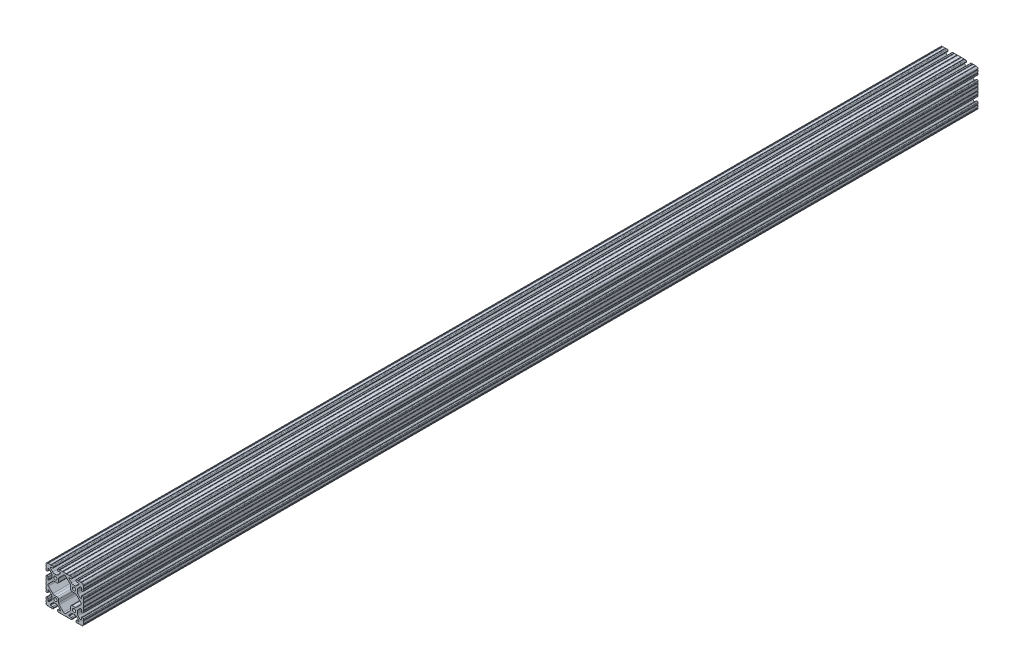
SolidWorks part; units mm, degrees
material "6105-T5 Aluminum"
ref_plane "Front Plane" through (0, 0, 0) normal (0, 0, 1) x (1, 0, 0)
ref_plane "Top Plane" through (0, 0, 0) normal (0, 1, 0) x (1, 0, 0)
ref_plane "Right Plane" through (0, 0, 0) normal (1, 0, 0) x (0, 0, -1)
sketch "Sketch1" plane through (0, 0, 0) normal (0, 0, 1) x (1, 0, 0)
  line L0 (15.487, 12.312) -> (20.9469, 12.312)
  line L1 (24.3055, 10.9208) -> (33.1609, 2.0655)
  line L2 (33.1609, -2.0655) -> (24.3055, -10.9208)
  line L3 (20.9469, -12.312) -> (15.487, -12.312)
  line L4 (12.312, -15.487) -> (12.312, -20.9469)
  line L5 (10.9208, -24.3055) -> (2.0655, -33.1609)
  line L6 (-2.0655, -33.1609) -> (-10.9208, -24.3055)
  line L7 (-12.312, -20.9469) -> (-12.312, -15.487)
  line L8 (-15.487, -12.312) -> (-20.9469, -12.312)
  line L9 (-24.3055, -10.9208) -> (-33.1609, -2.0655)
  line L10 (-33.1609, 2.0655) -> (-24.3055, 10.9208)
  line L11 (-20.9469, 12.312) -> (-15.487, 12.312)
  line L12 (-12.312, 15.487) -> (-12.312, 20.9469)
  line L13 (-10.9208, 24.3055) -> (-2.0655, 33.1609)
  line L14 (2.0655, 33.1609) -> (10.9208, 24.3055)
  line L15 (12.312, 20.9469) -> (12.312, 15.487)
  line L16 (-38.1, 3.2004) -> (-38.1, -3.2004)
  line L17 (-38.1, -4.7244) -> (-38.1, -9.5504)
  line L18 (-38.1, -11.0744) -> (-38.1, -13.4112)
  line L19 (-36.5252, -14.986) -> (-35.6108, -14.986)
  line L20 (-34.036, -13.4112) -> (-34.036, -9.652)
  line L21 (-33.147, -8.763) -> (-32.5789, -8.763)
  line L22 (-31.9503, -9.0234) -> (-27.1792, -13.7945)
  line L23 (-25.788, -17.1531) -> (-25.788, -20.9469)
  line L24 (-27.1792, -24.3055) -> (-31.9503, -29.0766)
  line L25 (-32.5789, -29.337) -> (-33.147, -29.337)
  line L26 (-34.036, -28.448) -> (-34.036, -24.6888)
  line L27 (-35.6108, -23.114) -> (-36.5252, -23.114)
  line L28 (-38.1, -24.6888) -> (-38.1, -27.0256)
  line L29 (-38.1, -28.5496) -> (-38.1, -33.3756)
  line L30 (-38.1, -34.8996) -> (-38.1, -34.925)
  line L31 (-34.925, -38.1) -> (-34.8996, -38.1)
  line L32 (-33.3756, -38.1) -> (-28.5496, -38.1)
  line L33 (-27.0256, -38.1) -> (-24.6888, -38.1)
  line L34 (-23.114, -36.5252) -> (-23.114, -35.6108)
  line L35 (-24.6888, -34.036) -> (-28.448, -34.036)
  line L36 (-29.337, -33.147) -> (-29.337, -32.5789)
  line L37 (-29.0766, -31.9503) -> (-24.3055, -27.1792)
  line L38 (-20.9469, -25.788) -> (-17.1531, -25.788)
  line L39 (-13.7945, -27.1792) -> (-9.0234, -31.9503)
  line L40 (-8.763, -32.5789) -> (-8.763, -33.147)
  line L41 (-9.652, -34.036) -> (-13.4112, -34.036)
  line L42 (-14.986, -35.6108) -> (-14.986, -36.5252)
  line L43 (-13.4112, -38.1) -> (-11.0744, -38.1)
  line L44 (-9.5504, -38.1) -> (-4.7244, -38.1)
  line L45 (-3.2004, -38.1) -> (3.2004, -38.1)
  line L46 (4.7244, -38.1) -> (9.5504, -38.1)
  line L47 (11.0744, -38.1) -> (13.4112, -38.1)
  line L48 (14.986, -36.5252) -> (14.986, -35.6108)
  line L49 (13.4112, -34.036) -> (9.652, -34.036)
  line L50 (8.763, -33.147) -> (8.763, -32.5789)
  line L51 (9.0234, -31.9503) -> (13.7945, -27.1792)
  line L52 (17.1531, -25.788) -> (20.9469, -25.788)
  line L53 (24.3055, -27.1792) -> (29.0766, -31.9503)
  line L54 (29.337, -32.5789) -> (29.337, -33.147)
  line L55 (28.448, -34.036) -> (24.6888, -34.036)
  line L56 (23.114, -35.6108) -> (23.114, -36.5252)
  line L57 (24.6888, -38.1) -> (27.0256, -38.1)
  line L58 (28.5496, -38.1) -> (33.3756, -38.1)
  line L59 (34.8996, -38.1) -> (34.925, -38.1)
  line L60 (38.1, -34.925) -> (38.1, -34.8996)
  line L61 (38.1, -33.3756) -> (38.1, -28.5496)
  line L62 (38.1, -27.0256) -> (38.1, -24.6888)
  line L63 (36.5252, -23.114) -> (35.6108, -23.114)
  line L64 (34.036, -24.6888) -> (34.036, -28.448)
  line L65 (33.147, -29.337) -> (32.5789, -29.337)
  line L66 (31.9503, -29.0766) -> (27.1792, -24.3055)
  line L67 (25.788, -20.9469) -> (25.788, -17.1531)
  line L68 (27.1792, -13.7945) -> (31.9503, -9.0234)
  line L69 (32.5789, -8.763) -> (33.147, -8.763)
  line L70 (34.036, -9.652) -> (34.036, -13.4112)
  line L71 (35.6108, -14.986) -> (36.5252, -14.986)
  line L72 (38.1, -13.4112) -> (38.1, -11.0744)
  line L73 (38.1, -9.5504) -> (38.1, -4.7244)
  line L74 (38.1, -3.2004) -> (38.1, 3.2004)
  line L75 (38.1, 4.7244) -> (38.1, 9.5504)
  line L76 (38.1, 11.0744) -> (38.1, 13.4112)
  line L77 (36.5252, 14.986) -> (35.6108, 14.986)
  line L78 (34.036, 13.4112) -> (34.036, 9.652)
  line L79 (33.147, 8.763) -> (32.5789, 8.763)
  line L80 (31.9503, 9.0234) -> (27.1792, 13.7945)
  line L81 (25.788, 17.1531) -> (25.788, 20.9469)
  line L82 (27.1792, 24.3055) -> (31.9503, 29.0766)
  line L83 (32.5789, 29.337) -> (33.147, 29.337)
  line L84 (34.036, 28.448) -> (34.036, 24.6888)
  line L85 (35.6108, 23.114) -> (36.5252, 23.114)
  line L86 (38.1, 24.6888) -> (38.1, 27.0256)
  line L87 (38.1, 28.5496) -> (38.1, 33.3756)
  line L88 (38.1, 34.8996) -> (38.1, 34.925)
  line L89 (34.925, 38.1) -> (34.8996, 38.1)
  line L90 (33.3756, 38.1) -> (28.5496, 38.1)
  line L91 (27.0256, 38.1) -> (24.6888, 38.1)
  line L92 (23.114, 36.5252) -> (23.114, 35.6108)
  line L93 (24.6888, 34.036) -> (28.448, 34.036)
  line L94 (29.337, 33.147) -> (29.337, 32.5789)
  line L95 (29.0766, 31.9503) -> (24.3055, 27.1792)
  line L96 (20.9469, 25.788) -> (17.1531, 25.788)
  line L97 (13.7945, 27.1792) -> (9.0234, 31.9503)
  line L98 (8.763, 32.5789) -> (8.763, 33.147)
  line L99 (9.652, 34.036) -> (13.4112, 34.036)
  line L100 (14.986, 35.6108) -> (14.986, 36.5252)
  line L101 (13.4112, 38.1) -> (11.0744, 38.1)
  line L102 (9.5504, 38.1) -> (4.7244, 38.1)
  line L103 (3.2004, 38.1) -> (-3.2004, 38.1)
  line L104 (-4.7244, 38.1) -> (-9.5504, 38.1)
  line L105 (-11.0744, 38.1) -> (-13.4112, 38.1)
  line L106 (-14.986, 36.5252) -> (-14.986, 35.6108)
  line L107 (-13.4112, 34.036) -> (-9.652, 34.036)
  line L108 (-8.763, 33.147) -> (-8.763, 32.5789)
  line L109 (-9.0234, 31.9503) -> (-13.7945, 27.1792)
  line L110 (-17.1531, 25.788) -> (-20.9469, 25.788)
  line L111 (-24.3055, 27.1792) -> (-29.0766, 31.9503)
  line L112 (-29.337, 32.5789) -> (-29.337, 33.147)
  line L113 (-28.448, 34.036) -> (-24.6888, 34.036)
  line L114 (-23.114, 35.6108) -> (-23.114, 36.5252)
  line L115 (-24.6888, 38.1) -> (-27.0256, 38.1)
  line L116 (-28.5496, 38.1) -> (-33.3756, 38.1)
  line L117 (-34.8996, 38.1) -> (-34.925, 38.1)
  line L118 (-38.1, 34.925) -> (-38.1, 34.8996)
  line L119 (-38.1, 33.3756) -> (-38.1, 28.5496)
  line L120 (-38.1, 27.0256) -> (-38.1, 24.6888)
  line L121 (-36.5252, 23.114) -> (-35.6108, 23.114)
  line L122 (-34.036, 24.6888) -> (-34.036, 28.448)
  line L123 (-33.147, 29.337) -> (-32.5789, 29.337)
  line L124 (-31.9503, 29.0766) -> (-27.1792, 24.3055)
  line L125 (-25.788, 20.9469) -> (-25.788, 17.1531)
  line L126 (-27.1792, 13.7945) -> (-31.9503, 9.0234)
  line L127 (-32.5789, 8.763) -> (-33.147, 8.763)
  line L128 (-34.036, 9.652) -> (-34.036, 13.4112)
  line L129 (-35.6108, 14.986) -> (-36.5252, 14.986)
  line L130 (-38.1, 13.4112) -> (-38.1, 11.0744)
  line L131 (-38.1, 9.5504) -> (-38.1, 4.7244)
  circle A0 centre (-19.05, 19.05) radius 3.3274
  circle A1 centre (-19.05, -19.05) radius 3.3274
  circle A2 centre (19.05, -19.05) radius 3.3274
  circle A3 centre (19.05, 19.05) radius 3.3274
  arc A4 (12.312, 15.487) -> (15.487, 12.312) centre (15.487, 15.487) ccw
  arc A5 (24.3055, 10.9208) -> (20.9469, 12.312) centre (20.9469, 7.5622) ccw
  arc A6 (33.1609, -2.0655) -> (33.1609, 2.0655) centre (31.0954, 0) ccw
  arc A7 (20.9469, -12.312) -> (24.3055, -10.9208) centre (20.9469, -7.5622) ccw
  arc A8 (15.487, -12.312) -> (12.312, -15.487) centre (15.487, -15.487) ccw
  arc A9 (10.9208, -24.3055) -> (12.312, -20.9469) centre (7.5622, -20.9469) ccw
  arc A10 (-2.0655, -33.1609) -> (2.0655, -33.1609) centre (0, -31.0954) ccw
  arc A11 (-12.312, -20.9469) -> (-10.9208, -24.3055) centre (-7.5622, -20.9469) ccw
  arc A12 (-12.312, -15.487) -> (-15.487, -12.312) centre (-15.487, -15.487) ccw
  arc A13 (-24.3055, -10.9208) -> (-20.9469, -12.312) centre (-20.9469, -7.5622) ccw
  arc A14 (-33.1609, 2.0655) -> (-33.1609, -2.0655) centre (-31.0954, 0) ccw
  arc A15 (-20.9469, 12.312) -> (-24.3055, 10.9208) centre (-20.9469, 7.5622) ccw
  arc A16 (-15.487, 12.312) -> (-12.312, 15.487) centre (-15.487, 15.487) ccw
  arc A17 (-10.9208, 24.3055) -> (-12.312, 20.9469) centre (-7.5622, 20.9469) ccw
  arc A18 (2.0655, 33.1609) -> (-2.0655, 33.1609) centre (0, 31.0954) ccw
  arc A19 (12.312, 20.9469) -> (10.9208, 24.3055) centre (7.5622, 20.9469) ccw
  arc A20 (-38.1, -4.7244) -> (-38.1, -3.2004) centre (-38.1, -3.9624) ccw
  arc A21 (-38.1, -11.0744) -> (-38.1, -9.5504) centre (-38.1, -10.3124) ccw
  arc A22 (-38.1, -13.4112) -> (-36.5252, -14.986) centre (-36.5252, -13.4112) ccw
  arc A23 (-35.6108, -14.986) -> (-34.036, -13.4112) centre (-35.6108, -13.4112) ccw
  arc A24 (-33.147, -8.763) -> (-34.036, -9.652) centre (-33.147, -9.652) ccw
  arc A25 (-31.9503, -9.0234) -> (-32.5789, -8.763) centre (-32.5789, -9.652) ccw
  arc A26 (-25.788, -17.1531) -> (-27.1792, -13.7945) centre (-30.5378, -17.1531) ccw
  arc A27 (-27.1792, -24.3055) -> (-25.788, -20.9469) centre (-30.5378, -20.9469) ccw
  arc A28 (-32.5789, -29.337) -> (-31.9503, -29.0766) centre (-32.5789, -28.448) ccw
  arc A29 (-34.036, -28.448) -> (-33.147, -29.337) centre (-33.147, -28.448) ccw
  arc A30 (-34.036, -24.6888) -> (-35.6108, -23.114) centre (-35.6108, -24.6888) ccw
  arc A31 (-36.5252, -23.114) -> (-38.1, -24.6888) centre (-36.5252, -24.6888) ccw
  arc A32 (-38.1, -28.5496) -> (-38.1, -27.0256) centre (-38.1, -27.7876) ccw
  arc A33 (-38.1, -34.8996) -> (-38.1, -33.3756) centre (-38.1, -34.1376) ccw
  arc A34 (-38.1, -34.925) -> (-34.925, -38.1) centre (-34.925, -34.925) ccw
  arc A35 (-33.3756, -38.1) -> (-34.8996, -38.1) centre (-34.1376, -38.1) ccw
  arc A36 (-27.0256, -38.1) -> (-28.5496, -38.1) centre (-27.7876, -38.1) ccw
  arc A37 (-24.6888, -38.1) -> (-23.114, -36.5252) centre (-24.6888, -36.5252) ccw
  arc A38 (-23.114, -35.6108) -> (-24.6888, -34.036) centre (-24.6888, -35.6108) ccw
  arc A39 (-29.337, -33.147) -> (-28.448, -34.036) centre (-28.448, -33.147) ccw
  arc A40 (-29.0766, -31.9503) -> (-29.337, -32.5789) centre (-28.448, -32.5789) ccw
  arc A41 (-20.9469, -25.788) -> (-24.3055, -27.1792) centre (-20.9469, -30.5378) ccw
  arc A42 (-13.7945, -27.1792) -> (-17.1531, -25.788) centre (-17.1531, -30.5378) ccw
  arc A43 (-8.763, -32.5789) -> (-9.0234, -31.9503) centre (-9.652, -32.5789) ccw
  arc A44 (-9.652, -34.036) -> (-8.763, -33.147) centre (-9.652, -33.147) ccw
  arc A45 (-13.4112, -34.036) -> (-14.986, -35.6108) centre (-13.4112, -35.6108) ccw
  arc A46 (-14.986, -36.5252) -> (-13.4112, -38.1) centre (-13.4112, -36.5252) ccw
  arc A47 (-9.5504, -38.1) -> (-11.0744, -38.1) centre (-10.3124, -38.1) ccw
  arc A48 (-3.2004, -38.1) -> (-4.7244, -38.1) centre (-3.9624, -38.1) ccw
  arc A49 (4.7244, -38.1) -> (3.2004, -38.1) centre (3.9624, -38.1) ccw
  arc A50 (11.0744, -38.1) -> (9.5504, -38.1) centre (10.3124, -38.1) ccw
  arc A51 (13.4112, -38.1) -> (14.986, -36.5252) centre (13.4112, -36.5252) ccw
  arc A52 (14.986, -35.6108) -> (13.4112, -34.036) centre (13.4112, -35.6108) ccw
  arc A53 (8.763, -33.147) -> (9.652, -34.036) centre (9.652, -33.147) ccw
  arc A54 (9.0234, -31.9503) -> (8.763, -32.5789) centre (9.652, -32.5789) ccw
  arc A55 (17.1531, -25.788) -> (13.7945, -27.1792) centre (17.1531, -30.5378) ccw
  arc A56 (24.3055, -27.1792) -> (20.9469, -25.788) centre (20.9469, -30.5378) ccw
  arc A57 (29.337, -32.5789) -> (29.0766, -31.9503) centre (28.448, -32.5789) ccw
  arc A58 (28.448, -34.036) -> (29.337, -33.147) centre (28.448, -33.147) ccw
  arc A59 (24.6888, -34.036) -> (23.114, -35.6108) centre (24.6888, -35.6108) ccw
  arc A60 (23.114, -36.5252) -> (24.6888, -38.1) centre (24.6888, -36.5252) ccw
  arc A61 (28.5496, -38.1) -> (27.0256, -38.1) centre (27.7876, -38.1) ccw
  arc A62 (34.8996, -38.1) -> (33.3756, -38.1) centre (34.1376, -38.1) ccw
  arc A63 (34.925, -38.1) -> (38.1, -34.925) centre (34.925, -34.925) ccw
  arc A64 (38.1, -33.3756) -> (38.1, -34.8996) centre (38.1, -34.1376) ccw
  arc A65 (38.1, -27.0256) -> (38.1, -28.5496) centre (38.1, -27.7876) ccw
  arc A66 (38.1, -24.6888) -> (36.5252, -23.114) centre (36.5252, -24.6888) ccw
  arc A67 (35.6108, -23.114) -> (34.036, -24.6888) centre (35.6108, -24.6888) ccw
  arc A68 (33.147, -29.337) -> (34.036, -28.448) centre (33.147, -28.448) ccw
  arc A69 (31.9503, -29.0766) -> (32.5789, -29.337) centre (32.5789, -28.448) ccw
  arc A70 (25.788, -20.9469) -> (27.1792, -24.3055) centre (30.5378, -20.9469) ccw
  arc A71 (27.1792, -13.7945) -> (25.788, -17.1531) centre (30.5378, -17.1531) ccw
  arc A72 (32.5789, -8.763) -> (31.9503, -9.0234) centre (32.5789, -9.652) ccw
  arc A73 (34.036, -9.652) -> (33.147, -8.763) centre (33.147, -9.652) ccw
  arc A74 (34.036, -13.4112) -> (35.6108, -14.986) centre (35.6108, -13.4112) ccw
  arc A75 (36.5252, -14.986) -> (38.1, -13.4112) centre (36.5252, -13.4112) ccw
  arc A76 (38.1, -9.5504) -> (38.1, -11.0744) centre (38.1, -10.3124) ccw
  arc A77 (38.1, -3.2004) -> (38.1, -4.7244) centre (38.1, -3.9624) ccw
  arc A78 (38.1, 4.7244) -> (38.1, 3.2004) centre (38.1, 3.9624) ccw
  arc A79 (38.1, 11.0744) -> (38.1, 9.5504) centre (38.1, 10.3124) ccw
  arc A80 (38.1, 13.4112) -> (36.5252, 14.986) centre (36.5252, 13.4112) ccw
  arc A81 (35.6108, 14.986) -> (34.036, 13.4112) centre (35.6108, 13.4112) ccw
  arc A82 (33.147, 8.763) -> (34.036, 9.652) centre (33.147, 9.652) ccw
  arc A83 (31.9503, 9.0234) -> (32.5789, 8.763) centre (32.5789, 9.652) ccw
  arc A84 (25.788, 17.1531) -> (27.1792, 13.7945) centre (30.5378, 17.1531) ccw
  arc A85 (27.1792, 24.3055) -> (25.788, 20.9469) centre (30.5378, 20.9469) ccw
  arc A86 (32.5789, 29.337) -> (31.9503, 29.0766) centre (32.5789, 28.448) ccw
  arc A87 (34.036, 28.448) -> (33.147, 29.337) centre (33.147, 28.448) ccw
  arc A88 (34.036, 24.6888) -> (35.6108, 23.114) centre (35.6108, 24.6888) ccw
  arc A89 (36.5252, 23.114) -> (38.1, 24.6888) centre (36.5252, 24.6888) ccw
  arc A90 (38.1, 28.5496) -> (38.1, 27.0256) centre (38.1, 27.7876) ccw
  arc A91 (38.1, 34.8996) -> (38.1, 33.3756) centre (38.1, 34.1376) ccw
  arc A92 (38.1, 34.925) -> (34.925, 38.1) centre (34.925, 34.925) ccw
  arc A93 (33.3756, 38.1) -> (34.8996, 38.1) centre (34.1376, 38.1) ccw
  arc A94 (27.0256, 38.1) -> (28.5496, 38.1) centre (27.7876, 38.1) ccw
  arc A95 (24.6888, 38.1) -> (23.114, 36.5252) centre (24.6888, 36.5252) ccw
  arc A96 (23.114, 35.6108) -> (24.6888, 34.036) centre (24.6888, 35.6108) ccw
  arc A97 (29.337, 33.147) -> (28.448, 34.036) centre (28.448, 33.147) ccw
  arc A98 (29.0766, 31.9503) -> (29.337, 32.5789) centre (28.448, 32.5789) ccw
  arc A99 (20.9469, 25.788) -> (24.3055, 27.1792) centre (20.9469, 30.5378) ccw
  arc A100 (13.7945, 27.1792) -> (17.1531, 25.788) centre (17.1531, 30.5378) ccw
  arc A101 (8.763, 32.5789) -> (9.0234, 31.9503) centre (9.652, 32.5789) ccw
  arc A102 (9.652, 34.036) -> (8.763, 33.147) centre (9.652, 33.147) ccw
  arc A103 (13.4112, 34.036) -> (14.986, 35.6108) centre (13.4112, 35.6108) ccw
  arc A104 (14.986, 36.5252) -> (13.4112, 38.1) centre (13.4112, 36.5252) ccw
  arc A105 (9.5504, 38.1) -> (11.0744, 38.1) centre (10.3124, 38.1) ccw
  arc A106 (3.2004, 38.1) -> (4.7244, 38.1) centre (3.9624, 38.1) ccw
  arc A107 (-4.7244, 38.1) -> (-3.2004, 38.1) centre (-3.9624, 38.1) ccw
  arc A108 (-11.0744, 38.1) -> (-9.5504, 38.1) centre (-10.3124, 38.1) ccw
  arc A109 (-13.4112, 38.1) -> (-14.986, 36.5252) centre (-13.4112, 36.5252) ccw
  arc A110 (-14.986, 35.6108) -> (-13.4112, 34.036) centre (-13.4112, 35.6108) ccw
  arc A111 (-8.763, 33.147) -> (-9.652, 34.036) centre (-9.652, 33.147) ccw
  arc A112 (-9.0234, 31.9503) -> (-8.763, 32.5789) centre (-9.652, 32.5789) ccw
  arc A113 (-17.1531, 25.788) -> (-13.7945, 27.1792) centre (-17.1531, 30.5378) ccw
  arc A114 (-24.3055, 27.1792) -> (-20.9469, 25.788) centre (-20.9469, 30.5378) ccw
  arc A115 (-29.337, 32.5789) -> (-29.0766, 31.9503) centre (-28.448, 32.5789) ccw
  arc A116 (-28.448, 34.036) -> (-29.337, 33.147) centre (-28.448, 33.147) ccw
  arc A117 (-24.6888, 34.036) -> (-23.114, 35.6108) centre (-24.6888, 35.6108) ccw
  arc A118 (-23.114, 36.5252) -> (-24.6888, 38.1) centre (-24.6888, 36.5252) ccw
  arc A119 (-28.5496, 38.1) -> (-27.0256, 38.1) centre (-27.7876, 38.1) ccw
  arc A120 (-34.8996, 38.1) -> (-33.3756, 38.1) centre (-34.1376, 38.1) ccw
  arc A121 (-34.925, 38.1) -> (-38.1, 34.925) centre (-34.925, 34.925) ccw
  arc A122 (-38.1, 33.3756) -> (-38.1, 34.8996) centre (-38.1, 34.1376) ccw
  arc A123 (-38.1, 27.0256) -> (-38.1, 28.5496) centre (-38.1, 27.7876) ccw
  arc A124 (-38.1, 24.6888) -> (-36.5252, 23.114) centre (-36.5252, 24.6888) ccw
  arc A125 (-35.6108, 23.114) -> (-34.036, 24.6888) centre (-35.6108, 24.6888) ccw
  arc A126 (-33.147, 29.337) -> (-34.036, 28.448) centre (-33.147, 28.448) ccw
  arc A127 (-31.9503, 29.0766) -> (-32.5789, 29.337) centre (-32.5789, 28.448) ccw
  arc A128 (-25.788, 20.9469) -> (-27.1792, 24.3055) centre (-30.5378, 20.9469) ccw
  arc A129 (-27.1792, 13.7945) -> (-25.788, 17.1531) centre (-30.5378, 17.1531) ccw
  arc A130 (-32.5789, 8.763) -> (-31.9503, 9.0234) centre (-32.5789, 9.652) ccw
  arc A131 (-34.036, 9.652) -> (-33.147, 8.763) centre (-33.147, 9.652) ccw
  arc A132 (-34.036, 13.4112) -> (-35.6108, 14.986) centre (-35.6108, 13.4112) ccw
  arc A133 (-36.5252, 14.986) -> (-38.1, 13.4112) centre (-36.5252, 13.4112) ccw
  arc A134 (-38.1, 9.5504) -> (-38.1, 11.0744) centre (-38.1, 10.3124) ccw
  arc A135 (-38.1, 3.2004) -> (-38.1, 4.7244) centre (-38.1, 3.9624) ccw
  dimension "D1" = 19.05
  dimension "D2" = 19.05
  dimension "D3" = 19.05
  dimension "D4" = 19.05
extrude "Boss-Extrude1" add sketch "Sketch1" along normal blind 1828.8
